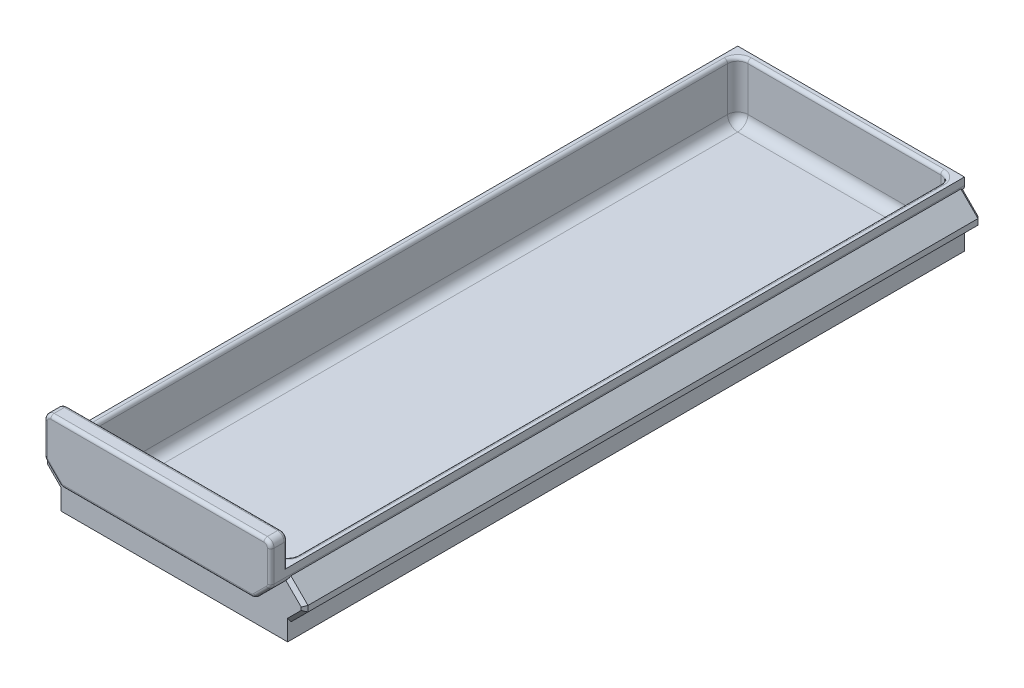
SolidWorks part; units mm, degrees
ref_plane "前视基准面" through (0, 0, 0) normal (0, 0, 1) x (1, 0, 0)
ref_plane "上视基准面" through (0, 0, 0) normal (0, 1, 0) x (1, 0, 0)
ref_plane "右视基准面" through (0, 0, 0) normal (1, 0, 0) x (0, 0, -1)
other "Configuration Table"
sketch "草图1" plane through (0, 0, 0) normal (0, 0, 1) x (1, 0, 0)
  line L0 (-73, 28) -> (-6, 28)
  line L1 (-73, 28) -> (-73, 32.6569)
  line L2 (-78, 37.6569) -> (-78, 39.3532)
  line L3 (-78, 39.3532) -> (-73, 44.3532)
  line L4 (-73, 44.3532) -> (-73, 47)
  line L5 (-77, 47) -> (77, 47) construction
  line L6 (-73, 47) -> (-6, 47)
  line L7 (-39.5, 47) -> (-39.5, 2.5589) construction
  line L9 (-83, 41) -> (-77, 47) construction
  line L10 (-83, 37) -> (-83, 41) construction
  line L11 (-74, 18) -> (-74, 23) construction
  line L12 (-73, 32.6569) -> (-78, 37.6569)
  line L16 (-77, 31) -> (-83, 37) construction
  line L17 (-6, 32.6569) -> (-1, 37.6569)
  line L18 (-6, 44.3532) -> (-6, 47)
  line L19 (-1, 39.3532) -> (-6, 44.3532)
  line L20 (-1, 37.6569) -> (-1, 39.3532)
  line L21 (-6, 28) -> (-6, 32.6569)
  point P25 (-39.5, 28)
  dimension "D1" = 19
  dimension "D2" = 1
  dimension "D3" = 5
  dimension "D4" = 4.7
  dimension "D5" = 1
  dimension "D6" = 4
  dimension "D7" = 77
extrude "凸台-拉伸1" add sketch "草图1" against normal blind 200
sketch "草图2" plane through (0, 47, 0) normal (0, 1, 0) x (1, 0, 0)
  line L8 (-71, 2) -> (-8, 2)
  line L9 (-8, 2) -> (-8, 198)
  line L10 (-8, 198) -> (-71, 198)
  line L11 (-71, 198) -> (-71, 2)
  line L12 (-71, 2) -> (-8, 2)
  line L13 (-8, 2) -> (-8, 198)
  line L14 (-8, 198) -> (-71, 198)
  line L15 (-71, 198) -> (-71, 2)
  dimension "D1" = 2
extrude "切除-拉伸1" cut sketch "草图2" against normal offset from surface (17 mm away) 2 up to face at (-39.5, 28, -100)
sketch "草图3" plane through (0, 0, 0) normal (0, 0, 1) x (1, 0, 0)
  line L0 (87.5, 56) -> (-87.5, 56) construction
  line L1 (-73, 39) -> (-6, 39)
  line L2 (-73, 39) -> (-73, 56)
  line L3 (-73, 56) -> (-6, 56)
  line L4 (-6, 39) -> (-6, 56)
  line L5 (-73, 47) -> (-73, 44.3532) construction
  line L6 (-6, 44.3532) -> (-6, 47) construction
  line L7 (-6, 47) -> (-73, 47) construction
  dimension "D1" = 8
extrude "凸台-拉伸2" add sketch "草图3" along normal blind 5
chamfer "倒角1" distance 5 angle 45 2 edges at (-6, 39, 2.5) (-73, 39, 2.5)
fillet "圆角1" radius 2 6 edges at (-6, 56, 2.5) (-6, 44, 2.5) (-11, 39, 2.5) (-68, 39, 2.5) (-73, 44, 2.5) (-73, 56, 2.5)
fillet "圆角2" radius 1 17 edges at (-6, 50.5, 0) (-6.5858, 55.4142, 0) (-73, 50.5, 0) (-72.4142, 55.4142, 0) (-6.5858, 55.4142, 5) (-6, 49.4142, 5) (-6.1522, 44.0631, 5) (-8.5, 41.5, 5) (-11.0631, 39.1522, 5) (-39.5, 39, 5) (-67.9369, 39.1522, 5) (-70.5, 41.5, 5) (-72.8478, 44.0631, 5) (-73, 49.4142, 5) (-72.4142, 55.4142, 5) (-39.5, 56, 0) (-39.5, 56, 5)
fillet "圆角3" radius 3 8 edges at (-39.5, 30, -198) (-8, 30, -100) (-39.5, 30, -2) (-71, 30, -100) (-8, 38.5, -2) (-8, 38.5, -198) (-71, 38.5, -2) (-71, 38.5, -198)
fillet "圆角4" radius 1 8 edges at (-8.8787, 47, -197.1213) (-8, 47, -100) (-8.8787, 47, -2.8787) (-39.5, 47, -2) (-70.1213, 47, -2.8787) (-71, 47, -100) (-70.1213, 47, -197.1213) (-39.5, 47, -198)
chamfer "倒角2" distance 1 angle 45 12 edges at (-75.4768, 41.8764, 0) (-78, 38.505, 0) (-75.5, 35.1569, 0) (-3.5232, 41.8764, 0) (-1, 38.505, 0) (-3.5, 35.1569, 0) (-3.5, 35.1569, -200) (-3.5232, 41.8764, -200) (-1, 38.505, -200) (-75.5, 35.1569, -200) (-78, 38.505, -200) (-75.4768, 41.8764, -200)
